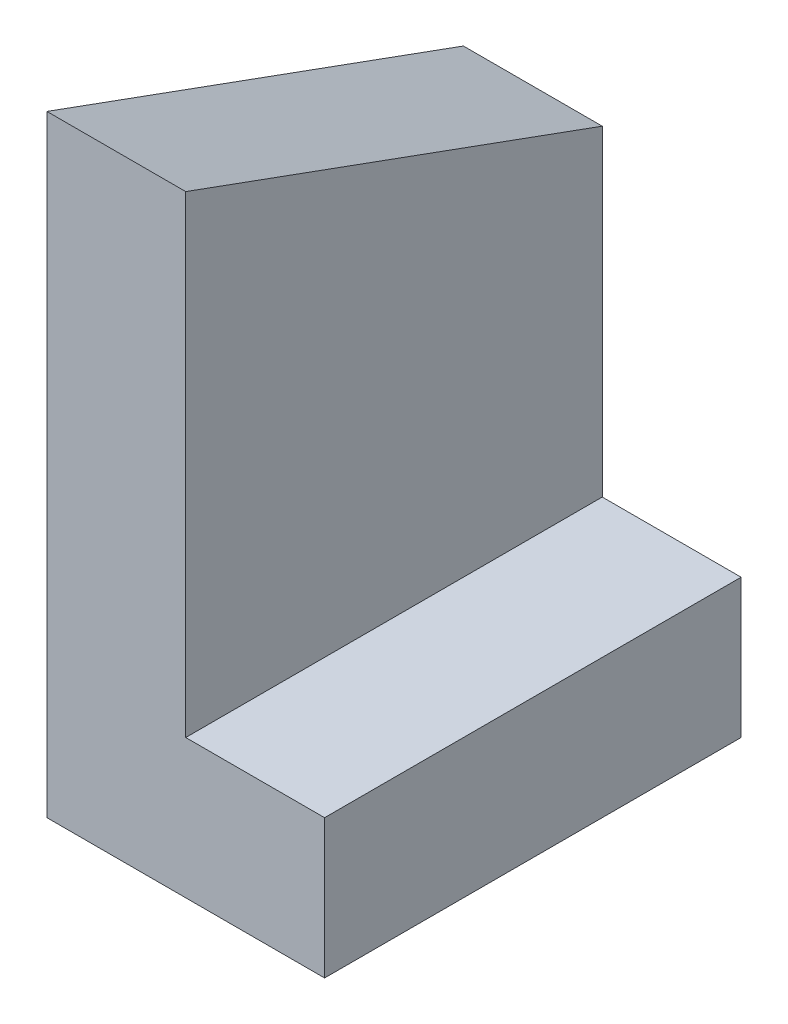
SolidWorks part; units mm, degrees
ref_plane "Front Plane" through (0, 0, 0) normal (0, 0, 1) x (1, 0, 0)
ref_plane "Top Plane" through (0, 0, 0) normal (0, 1, 0) x (1, 0, 0)
ref_plane "Right Plane" through (0, 0, 0) normal (1, 0, 0) x (0, 0, -1)
sketch "Sketch1" plane through (0, 0, 0) normal (0, 0, 1) x (1, 0, 0)
  line L0 (0, 0) -> (0, 25)
  line L1 (0, 0) -> (10, 0)
  line L2 (5, 5) -> (10, 5)
  line L3 (5, 5) -> (5, 25)
  line L4 (0, 25) -> (5, 25)
  line L5 (10, 5) -> (10, 0)
  dimension "D1" = 25
  dimension "D2" = 10
  dimension "D3" = 5
extrude "Boss-Extrude1" add sketch "Sketch1" along normal blind 15
sketch "Sketch2" plane through (5, 0, 0) normal (1, 0, 0) x (0, 0, -1)
  line L0 (-15, 22.0263) -> (-18.3281, 30.479)
  line L5 (-18.3281, 30.479) -> (8.325, 29.896)
  line L6 (8.325, 29.896) -> (0, 16.5668)
  line L8 (-7.5, 0) -> (-7.5, 37.8086) construction
  line L9 (-15, 0) -> (0, 0) construction
  line L10 (0, 16.5668) -> (-15, 22.0263)
extrude "Cut-Extrude1" cut sketch "Sketch2" against normal blind 10
